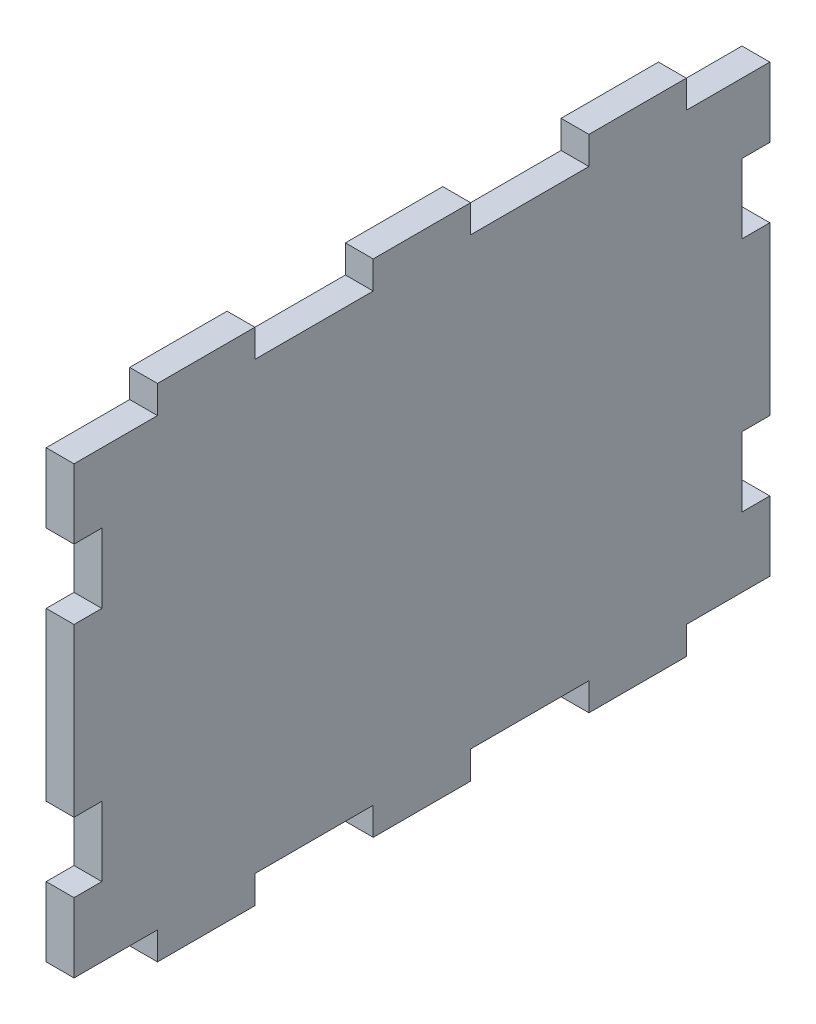
SolidWorks part; units mm, degrees
ref_plane "Front Plane" through (0, 0, 0) normal (0, 0, 1) x (1, 0, 0)
ref_plane "Top Plane" through (0, 0, 0) normal (0, 1, 0) x (1, 0, 0)
ref_plane "Right Plane" through (0, 0, 0) normal (1, 0, 0) x (0, 0, -1)
sketch "Sketch1" plane through (0, 0, 0) normal (1, 0, 0) x (0, 0, -1)
  line L1 (-25, 16) -> (25, 16)
  line L2 (-25, 16) -> (-25, -16)
  line L3 (-25, -16) -> (25, -16)
  line L4 (25, 16) -> (25, -16)
  line L5 (-25, 16) -> (25, -16) construction
  line L6 (-25, -16) -> (25, 16) construction
  line L7 (-19, -16) -> (-12, -16)
  line L8 (-19, -16) -> (-19, -18)
  line L9 (-19, -18) -> (-12, -18)
  line L10 (-12, -16) -> (-12, -18)
  line L11 (-3.5, -16) -> (3.5, -16)
  line L12 (-3.5, -16) -> (-3.5, -18)
  line L13 (-3.5, -18) -> (3.5, -18)
  line L14 (3.5, -16) -> (3.5, -18)
  line L15 (12, -16) -> (19, -16)
  line L16 (12, -16) -> (12, -18)
  line L17 (12, -18) -> (19, -18)
  line L18 (19, -16) -> (19, -18)
  line L19 (-19, 16) -> (-12, 16)
  line L20 (-19, 16) -> (-19, 18)
  line L21 (-19, 18) -> (-12, 18)
  line L22 (-12, 16) -> (-12, 18)
  line L23 (-3.5, 16) -> (3.5, 16)
  line L24 (-3.5, 16) -> (-3.5, 18)
  line L25 (-3.5, 18) -> (3.5, 18)
  line L26 (3.5, 16) -> (3.5, 18)
  line L27 (12, 16) -> (19, 16)
  line L28 (12, 16) -> (12, 18)
  line L29 (12, 18) -> (19, 18)
  line L30 (19, 16) -> (19, 18)
  line L31 (-25, -6) -> (-23, -6)
  line L32 (-25, -6) -> (-25, -11)
  line L33 (-25, -11) -> (-23, -11)
  line L34 (-23, -6) -> (-23, -11)
  line L35 (23, -6) -> (25, -6)
  line L36 (23, -6) -> (23, -11)
  line L37 (23, -11) -> (25, -11)
  line L38 (25, -6) -> (25, -11)
  line L39 (-25, 11) -> (-23, 11)
  line L40 (-25, 11) -> (-25, 6)
  line L41 (-25, 6) -> (-23, 6)
  line L42 (-23, 11) -> (-23, 6)
  line L43 (23, 11) -> (25, 11)
  line L44 (23, 11) -> (23, 6)
  line L45 (23, 6) -> (25, 6)
  line L46 (25, 11) -> (25, 6)
  point P0 (0, 0)
  dimension "D1" = 50
  dimension "D2" = 7
  dimension "D3" = 7
  dimension "D4" = 7
  dimension "D5" = 7
  dimension "D6" = 7
  dimension "D7" = 7
  dimension "D8" = 6
  dimension "D9" = 8.5
  dimension "D10" = 8.5
  dimension "D11" = 6
  dimension "D12" = 6
  dimension "D13" = 8.5
  dimension "D14" = 8.5
  dimension "D15" = 6
  dimension "D16" = 32
  dimension "D17" = 2
  dimension "D18" = 2
  dimension "D19" = 2
  dimension "D20" = 2
  dimension "D21" = 2
  dimension "D22" = 2
  dimension "D23" = 5
  dimension "D24" = 5
  dimension "D25" = 5
  dimension "D26" = 5
  dimension "D27" = 5
  dimension "D28" = 5
  dimension "D29" = 5
  dimension "D30" = 5
  dimension "D31" = 0
  dimension "D32" = 0
  dimension "D33" = 46
  dimension "D34" = 0
  dimension "D35" = 0
  dimension "D37" = 0
  dimension "D38" = 0
extrude "Boss-Extrude1" add sketch "Sketch1" along normal blind 2 contours L4 L1 L2 L3 | L1 L26 L25 L24 | L1 L30 L29 L28 | L18 L3 L16 L17 | L14 L3 L12 L13 | L10 L3 L8 L9 | L22 L21 L20 L19
